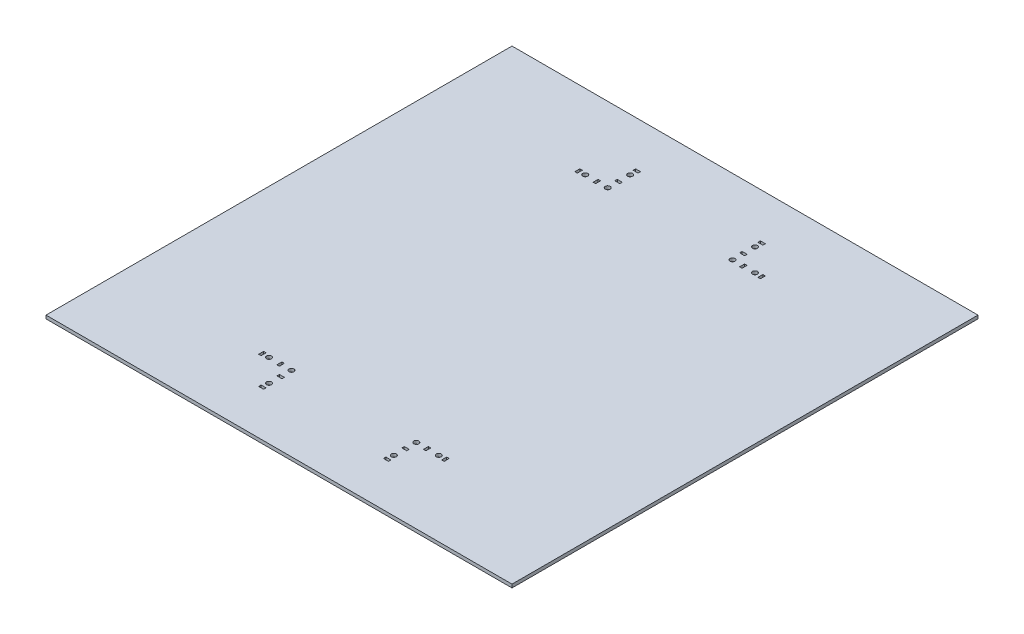
SolidWorks part; units mm, degrees
ref_plane "前视基准面" through (0, 0, 0) normal (0, 0, 1) x (1, 0, 0)
ref_plane "上视基准面" through (0, 0, 0) normal (0, 1, 0) x (1, 0, 0)
ref_plane "右视基准面" through (0, 0, 0) normal (1, 0, 0) x (0, 0, -1)
sketch "草图1" plane through (0, 0, 0) normal (0, 1, 0) x (1, 0, 0)
  line L1 (-280, 280) -> (280, 280)
  line L2 (-280, 280) -> (-280, -280)
  line L3 (-280, -280) -> (280, -280)
  line L4 (280, 280) -> (280, -280)
  line L5 (-280, 280) -> (280, -280) construction
  line L6 (-280, -280) -> (280, 280) construction
  point P0 (0, 0)
  dimension "D1" = 560
  dimension "D2" = 560
extrude "凸台-拉伸1" add sketch "草图1" along normal blind 4
sketch "草图2" plane through (0, 4, 0) normal (0, 1, 0) x (1, 0, 0)
  line L0 (-371.9025, 0) -> (404.5534, 0) construction
  line L1 (0, 298.2387) -> (0, -294.2569) construction
  line L2 (280, 280) -> (-280, 280) construction
  line L3 (-75, 190) -> (-171.8254, 286.8254) construction
  line L4 (-72, 226.5) -> (-78, 223.5) construction
  line L5 (-86.5, 193) -> (-89.5, 193)
  line L6 (-86.5, 193) -> (-86.5, 187)
  line L7 (-86.5, 187) -> (-89.5, 187)
  line L8 (-89.5, 193) -> (-89.5, 187)
  line L9 (-86.5, 193) -> (-89.5, 187) construction
  line L10 (-86.5, 187) -> (-89.5, 193) construction
  line L11 (-111.5, 193) -> (-108.5, 193)
  line L12 (-111.5, 193) -> (-111.5, 187)
  line L13 (-111.5, 187) -> (-108.5, 187)
  line L14 (-108.5, 193) -> (-108.5, 187)
  line L15 (-111.5, 193) -> (-108.5, 187) construction
  line L16 (-111.5, 187) -> (-108.5, 193) construction
  line L17 (-78, 226.5) -> (-72, 223.5) construction
  line L18 (-72, 201.5) -> (-78, 204.5) construction
  line L19 (-78, 201.5) -> (-72, 204.5) construction
  line L20 (-78, 223.5) -> (-72, 223.5)
  line L21 (-72, 226.5) -> (-72, 223.5)
  line L22 (-78, 226.5) -> (-72, 226.5)
  line L23 (-78, 226.5) -> (-78, 223.5)
  line L24 (-78, 204.5) -> (-72, 204.5)
  line L25 (-72, 201.5) -> (-72, 204.5)
  line L26 (-78, 201.5) -> (-72, 201.5)
  line L27 (-78, 201.5) -> (-78, 204.5)
  line L28 (78, 201.5) -> (72, 204.5) construction
  line L29 (72, 201.5) -> (78, 204.5) construction
  line L30 (78, 226.5) -> (72, 223.5) construction
  line L31 (111.5, 187) -> (108.5, 193) construction
  line L32 (111.5, 193) -> (108.5, 187) construction
  line L33 (86.5, 187) -> (89.5, 193) construction
  line L34 (86.5, 193) -> (89.5, 187) construction
  line L35 (72, 226.5) -> (78, 223.5) construction
  line L36 (75, 190) -> (171.8254, 286.8254) construction
  line L37 (78, 201.5) -> (78, 204.5)
  line L38 (78, 201.5) -> (72, 201.5)
  line L39 (72, 201.5) -> (72, 204.5)
  line L40 (78, 204.5) -> (72, 204.5)
  line L41 (78, 226.5) -> (78, 223.5)
  line L42 (78, 226.5) -> (72, 226.5)
  line L43 (72, 226.5) -> (72, 223.5)
  line L44 (78, 223.5) -> (72, 223.5)
  line L45 (108.5, 193) -> (108.5, 187)
  line L46 (111.5, 187) -> (108.5, 187)
  line L47 (111.5, 193) -> (111.5, 187)
  line L48 (111.5, 193) -> (108.5, 193)
  line L49 (89.5, 193) -> (89.5, 187)
  line L50 (86.5, 187) -> (89.5, 187)
  line L51 (86.5, 193) -> (86.5, 187)
  line L52 (86.5, 193) -> (89.5, 193)
  line L53 (75, -190) -> (171.8254, -286.8254) construction
  line L54 (72, -226.5) -> (78, -223.5) construction
  line L55 (86.5, -193) -> (89.5, -187) construction
  line L56 (86.5, -187) -> (89.5, -193) construction
  line L57 (111.5, -193) -> (108.5, -187) construction
  line L58 (111.5, -187) -> (108.5, -193) construction
  line L59 (78, -226.5) -> (72, -223.5) construction
  line L60 (72, -201.5) -> (78, -204.5) construction
  line L61 (78, -201.5) -> (72, -204.5) construction
  line L62 (-78, -201.5) -> (-72, -204.5) construction
  line L63 (-72, -201.5) -> (-78, -204.5) construction
  line L64 (-78, -226.5) -> (-72, -223.5) construction
  line L65 (-111.5, -187) -> (-108.5, -193) construction
  line L66 (-111.5, -193) -> (-108.5, -187) construction
  line L67 (-86.5, -187) -> (-89.5, -193) construction
  line L68 (-86.5, -193) -> (-89.5, -187) construction
  line L69 (-72, -226.5) -> (-78, -223.5) construction
  line L70 (-75, -190) -> (-171.8254, -286.8254) construction
  line L71 (86.5, -193) -> (89.5, -193)
  line L72 (86.5, -193) -> (86.5, -187)
  line L73 (86.5, -187) -> (89.5, -187)
  line L74 (89.5, -193) -> (89.5, -187)
  line L75 (111.5, -193) -> (108.5, -193)
  line L76 (111.5, -193) -> (111.5, -187)
  line L77 (111.5, -187) -> (108.5, -187)
  line L78 (108.5, -193) -> (108.5, -187)
  line L79 (78, -223.5) -> (72, -223.5)
  line L80 (72, -226.5) -> (72, -223.5)
  line L81 (78, -226.5) -> (72, -226.5)
  line L82 (78, -226.5) -> (78, -223.5)
  line L83 (78, -204.5) -> (72, -204.5)
  line L84 (72, -201.5) -> (72, -204.5)
  line L85 (78, -201.5) -> (72, -201.5)
  line L86 (78, -201.5) -> (78, -204.5)
  line L87 (-78, -201.5) -> (-78, -204.5)
  line L88 (-78, -201.5) -> (-72, -201.5)
  line L89 (-72, -201.5) -> (-72, -204.5)
  line L90 (-78, -204.5) -> (-72, -204.5)
  line L91 (-78, -226.5) -> (-78, -223.5)
  line L92 (-78, -226.5) -> (-72, -226.5)
  line L93 (-72, -226.5) -> (-72, -223.5)
  line L94 (-78, -223.5) -> (-72, -223.5)
  line L95 (-108.5, -193) -> (-108.5, -187)
  line L96 (-111.5, -187) -> (-108.5, -187)
  line L97 (-111.5, -193) -> (-111.5, -187)
  line L98 (-111.5, -193) -> (-108.5, -193)
  line L99 (-89.5, -193) -> (-89.5, -187)
  line L100 (-86.5, -187) -> (-89.5, -187)
  line L101 (-86.5, -193) -> (-86.5, -187)
  line L102 (-86.5, -193) -> (-89.5, -193)
  circle A0 centre (-75, 190) radius 3
  circle A1 centre (-102, 190) radius 3
  circle A2 centre (-75, 217) radius 3
  circle A3 centre (75, 217) radius 3
  circle A4 centre (102, 190) radius 3
  circle A5 centre (75, 190) radius 3
  circle A6 centre (75, -190) radius 3
  circle A7 centre (102, -190) radius 3
  circle A8 centre (75, -217) radius 3
  circle A9 centre (-75, -217) radius 3
  circle A10 centre (-102, -190) radius 3
  circle A11 centre (-75, -190) radius 3
  point P9 (-88, 190)
  point P18 (-110, 190)
  point P33 (-75, 225)
  point P34 (-75, 203)
  point P58 (75, 203)
  point P59 (75, 225)
  point P60 (110, 190)
  point P61 (88, 190)
  point P108 (88, -190)
  point P109 (110, -190)
  point P110 (75, -225)
  point P111 (75, -203)
  point P112 (-75, -203)
  point P113 (-75, -225)
  point P114 (-110, -190)
  point P115 (-88, -190)
  dimension "D1" = 90
  dimension "D2" = 6
  dimension "D8" = 6
  dimension "D3" = 150
  dimension "D4" = 45
  dimension "D5" = 3
  dimension "D6" = 6
  dimension "D7" = 11.5
  dimension "D9" = 12.5
  dimension "D10" = 3
  dimension "D11" = 6
  dimension "D12" = 8
extrude "切除-拉伸1" cut sketch "草图2" against normal blind 4
